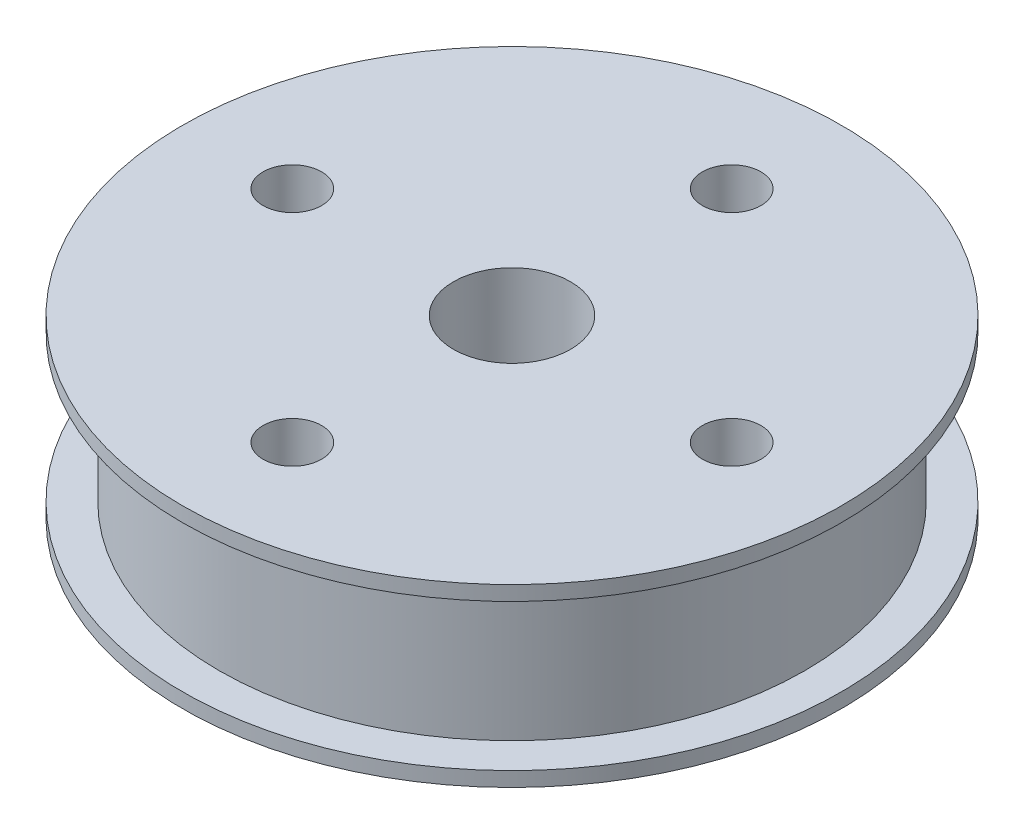
SolidWorks part; units mm, degrees
material "尼龙 6/10"
ref_plane "前视基准面" through (0, 0, 0) normal (0, 0, 1) x (1, 0, 0)
ref_plane "上视基准面" through (0, 0, 0) normal (0, 1, 0) x (1, 0, 0)
ref_plane "右视基准面" through (0, 0, 0) normal (1, 0, 0) x (0, 0, -1)
sketch "草图1" plane through (0, 0, 0) normal (0, 1, 0) x (1, 0, 0)
  circle A0 centre (0, 0) radius 20
  circle A1 centre (0, 15) radius 2
  circle A2 centre (15, 0) radius 2
  circle A3 centre (0, -15) radius 2
  circle A4 centre (-15, 0) radius 2
  circle A5 centre (0, 0) radius 4
  point P14 (0, 0)
  dimension "D1" = 40
  dimension "D2" = 4
  dimension "D3" = 15
  dimension "D5" = 8
  dimension "D4" = 4
extrude "凸台-拉伸1" add sketch "草图1" along normal blind 10
sketch "草图2" plane through (0, 10, 0) normal (0, 1, 0) x (1, 0, 0)
  circle A0 centre (0, 0) radius 22.5
  circle A1 centre (0, 0) radius 4
  circle A2 centre (-15, 0) radius 2
  circle A3 centre (0, 15) radius 2
  circle A4 centre (15, 0) radius 2
  circle A5 centre (0, -15) radius 2
  point P16 (0, 0)
  dimension "D1" = 45
  dimension "D2" = 4
  dimension "D3" = 8
  dimension "D5" = 15
  dimension "D4" = 4
extrude "凸台-拉伸2" add sketch "草图2" along normal blind 1
sketch "草图3" plane through (0, 0, 0) normal (0, -1, 0) x (1, 0, 0)
  circle A0 centre (0, 0) radius 22.5
  circle A1 centre (0, 0) radius 4
  circle A2 centre (15, 0) radius 2
  circle A3 centre (0, -15) radius 2
  circle A4 centre (-15, 0) radius 2
  circle A5 centre (0, 15) radius 2
  point P16 (0, 0)
  dimension "D1" = 45
  dimension "D2" = 8
  dimension "D3" = 4
  dimension "D4" = 4
extrude "凸台-拉伸3" add sketch "草图3" along normal blind 1
